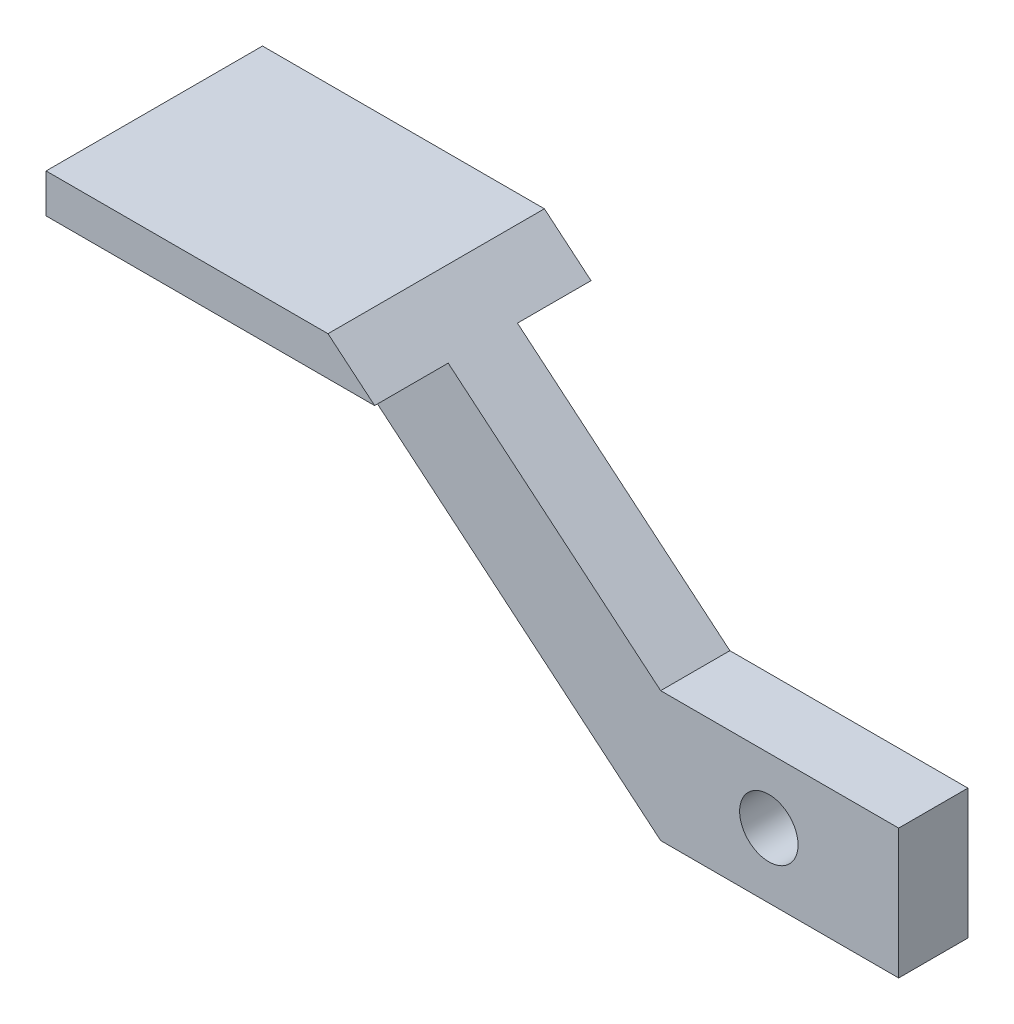
SolidWorks part; units mm, degrees
ref_plane "Płaszczyzna przednia" through (0, 0, 0) normal (0, 0, 1) x (1, 0, 0)
ref_plane "Płaszczyzna górna" through (0, 0, 0) normal (0, 1, 0) x (1, 0, 0)
ref_plane "Płaszczyzna prawa" through (0, 0, 0) normal (1, 0, 0) x (0, 0, -1)
sketch "Szkic1" plane through (0, 0, 0) normal (0, 0, 1) x (1, 0, 0)
  line L0 (0, 0) -> (-55, 0)
  line L1 (-55, 0) -> (-55, -30)
  line L2 (-55, -30) -> (0, -30)
  line L3 (0, -30) -> (0, 0)
  line L4 (-55, -30) -> (-140, 41)
  line L5 (-140, 41) -> (-180, 41)
  line L6 (-180, 41) -> (-180, 50)
  line L7 (-180, 50) -> (-114.8592, 50)
  line L8 (-114.8592, 50) -> (-55, 0)
  circle A0 centre (-30, -15) radius 6.75
  point P8 (0, -15)
  dimension "D3" = 13.5
  dimension "D1" = 55
  dimension "D2" = 30
  dimension "D4" = 9
  dimension "D5" = 180
  dimension "D6" = 80
  dimension "D7" = 40
  dimension "D8" = 30
extrude "Dodanie-wyciągnięcie1" add sketch "Szkic1" along normal mid plane 16 contours L2 L3 L0 L1 A0 | L8 L7 L6 L5 L4 L1
sketch "Szkic2" plane through (0, 0, 0) normal (0, 0, 1) x (1, 0, 0)
  line L0 (-140, 41) -> (-104.0845, 41)
  line L8 (-55, -30) -> (0, -30)
  line L9 (0, -30) -> (0, 0)
  line L10 (0, 0) -> (-55, 0)
  line L11 (-55, 0) -> (-114.8592, 50)
  line L12 (-114.8592, 50) -> (-180, 50)
  line L13 (-180, 50) -> (-180, 41)
  line L14 (-180, 41) -> (-140, 41)
  line L15 (-140, 41) -> (-55, -30)
  line L16 (-55, -30) -> (0, -30)
  line L17 (0, -30) -> (0, 0)
  line L18 (0, 0) -> (-55, 0)
  line L19 (-55, 0) -> (-114.8592, 50)
  line L20 (-114.8592, 50) -> (-180, 50)
  line L21 (-180, 50) -> (-180, 41)
  line L22 (-180, 41) -> (-140, 41)
  line L23 (-140, 41) -> (-55, -30)
  dimension "D1" = 0
extrude "Dodanie-wyciągnięcie2" add sketch "Szkic2" along normal mid plane 50 contours L21 L22 L0 L19 L20
